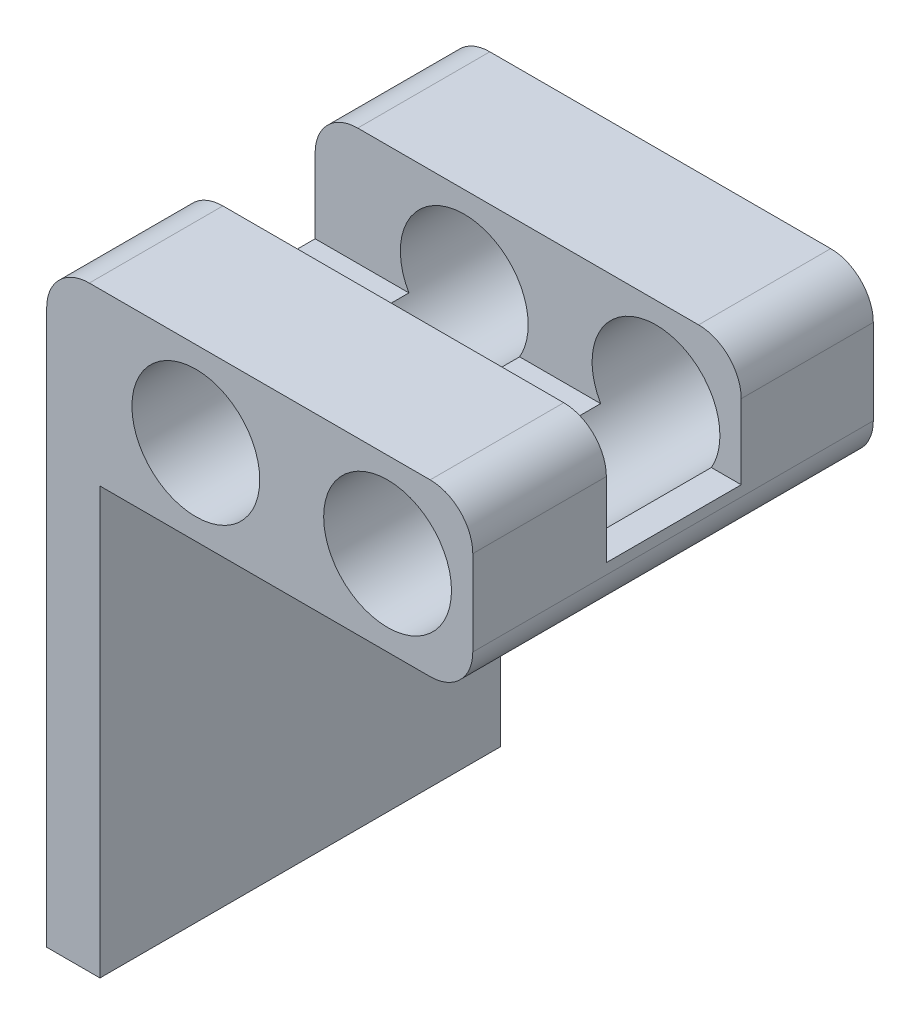
SolidWorks part; units mm, degrees
ref_plane "Front Plane" through (0, 0, 0) normal (0, 0, 1) x (1, 0, 0)
ref_plane "Top Plane" through (0, 0, 0) normal (0, 1, 0) x (1, 0, 0)
ref_plane "Right Plane" through (0, 0, 0) normal (1, 0, 0) x (0, 0, -1)
sketch "Sketch1" plane through (0, 0, 0) normal (1, 0, 0) x (0, 0, -1)
  line L1 (0, 0) -> (23.876, 0)
  line L2 (0, 0) -> (0, 25.4)
  line L3 (0, 25.4) -> (23.876, 25.4)
  line L4 (23.876, 0) -> (23.876, 25.4)
  dimension "D1" = 25.4
  dimension "D2" = 23.876
extrude "Boss-Extrude1" add sketch "Sketch1" along normal blind 3.175
sketch "Sketch2" plane through (0, 25.4, 0) normal (0, 1, 0) x (1, 0, 0)
  line L0 (3.175, 0) -> (0, 0) construction
  line L1 (0, 23.876) -> (25.4, 23.876)
  line L2 (0, 23.876) -> (0, 0)
  line L3 (0, 0) -> (25.4, 0)
  line L4 (25.4, 23.876) -> (25.4, 0)
  dimension "D1" = 25.4
extrude "Boss-Extrude2" add sketch "Sketch2" along normal blind 3.175
sketch "Sketch3" plane through (0, 28.575, 0) normal (0, 1, 0) x (1, 0, 0)
  line L0 (0, 23.876) -> (0, 0) construction
  line L1 (0, 0) -> (25.4, 0)
  line L2 (0, 0) -> (0, 7.9629)
  line L3 (0, 7.9629) -> (25.4, 7.9629)
  line L4 (25.4, 0) -> (25.4, 7.9629)
  line L5 (25.4, 0) -> (25.4, 23.876) construction
  line L7 (0, 23.876) -> (25.4, 23.876)
  line L8 (0, 23.876) -> (0, 16.002)
  line L9 (0, 16.002) -> (25.4, 16.002)
  line L10 (25.4, 23.876) -> (25.4, 16.002)
  line L12 (25.4, 23.876) -> (0, 23.876) construction
  line L13 (0, 0) -> (25.4, 0) construction
  dimension "D1" = 7.9629
  dimension "D2" = 7.874
extrude "Boss-Extrude3" add sketch "Sketch3" along normal blind 6.985
sketch "Sketch4" plane through (0, 0, 0) normal (0, 0, 1) x (1, 0, 0)
  line L0 (0, 35.56) -> (0, 0) construction
  line L1 (25.4, 30.48) -> (0, 30.48) construction
  line L2 (25.4, 35.56) -> (25.4, 25.4) construction
  circle A0 centre (8.89, 30.48) radius 3.81
  circle A1 centre (20.32, 30.48) radius 3.81
  dimension "D1" = 7.62
  dimension "D2" = 7.62
  dimension "D4" = 5.08
  dimension "D3" = 11.43
extrude "Cut-Extrude1" cut sketch "Sketch4" against normal through all and the other way through all
fillet "Fillet1" radius 2.54 2 edges at (0, 35.56, -19.939) (0, 35.56, -3.9815)
fillet "Fillet2" radius 2.54 1 edges at (25.4, 25.4, -11.938)
fillet "Fillet3" radius 2.54 2 edges at (25.4, 35.56, -19.939) (25.4, 35.56, -3.9815)
